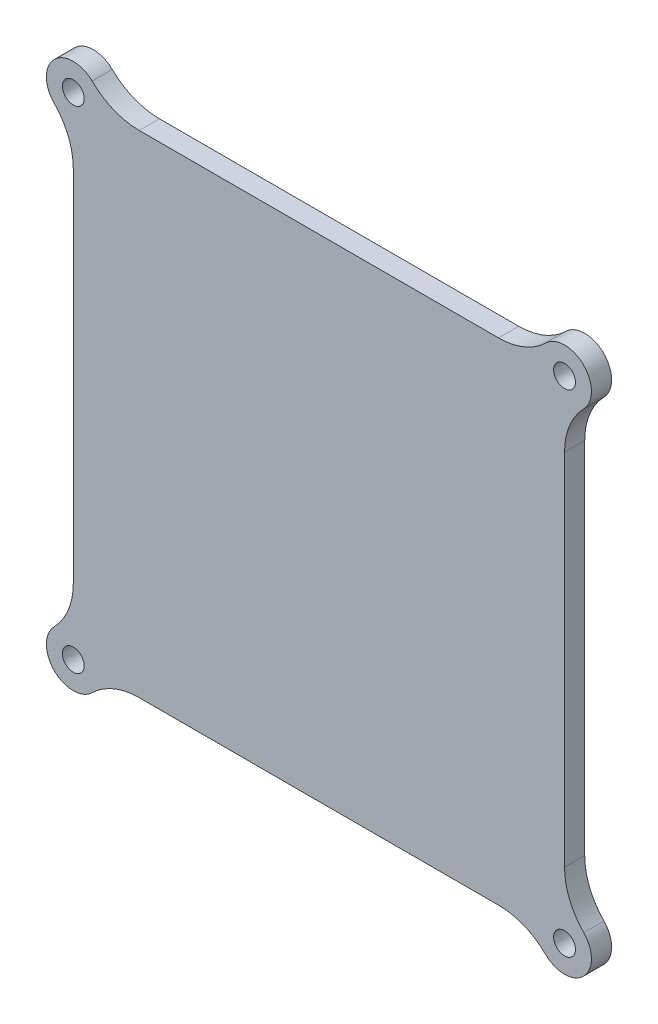
SolidWorks part; units mm, degrees
material "ABS"
ref_plane "Спереди" through (0, 0, 0) normal (0, 0, 1) x (1, 0, 0)
ref_plane "Сверху" through (0, 0, 0) normal (0, 1, 0) x (1, 0, 0)
ref_plane "Справа" through (0, 0, 0) normal (1, 0, 0) x (0, 0, -1)
sketch "Эскиз1" plane through (0, 0, 0) normal (0, 0, 1) x (1, 0, 0)
  line L1 (-36.5161, -36.5161) -> (36.5161, -36.5161)
  line L2 (-36.5161, -36.5161) -> (-36.5161, 36.5161)
  line L3 (-36.5161, 36.5161) -> (36.5161, 36.5161)
  line L4 (36.5161, -36.5161) -> (36.5161, 36.5161)
  line L5 (-36.5161, -36.5161) -> (36.5161, 36.5161) construction
  line L6 (-36.5161, 36.5161) -> (36.5161, -36.5161) construction
  circle A0 centre (-36.5161, 36.5161) radius 1.625
  arc A1 (-32.5161, 36.5161) -> (-36.5161, 32.5161) centre (-36.5161, 36.5161) ccw
  circle A2 centre (36.5161, 36.5161) radius 1.625
  arc A3 (36.5161, 32.5161) -> (32.5161, 36.5161) centre (36.5161, 36.5161) ccw
  circle A4 centre (36.5161, -36.5161) radius 1.625
  arc A5 (32.5161, -36.5161) -> (36.5161, -32.5161) centre (36.5161, -36.5161) ccw
  circle A6 centre (-36.5161, -36.5161) radius 1.625
  arc A7 (-36.5161, -32.5161) -> (-32.5161, -36.5161) centre (-36.5161, -36.5161) ccw
  point P0 (0, 0)
  point P8 (0, 0)
  point P20 (0, 0)
  dimension "D2" = 3.25
  dimension "D3" = 8
  dimension "D1" = 73.0321
  dimension "D4" = 4
extrude "Бобышка-Вытянуть1" add sketch "Эскиз1" along normal blind 3 contours A6 L1 A4 L4 A2 L3 A0 L2 | L3 A1 L2 A0 | L4 A3 L3 A2 | L1 A5 L4 A4 | L2 A7 L1 A6
fillet "Скругление1" radius 10 8 edges at (-32.5161, -36.5161, 1.5) (-36.5161, -32.5161, 1.5) (-32.5161, 36.5161, 1.5) (-36.5161, 32.5161, 1.5) (32.5161, 36.5161, 1.5) (36.5161, 32.5161, 1.5) (36.5161, -32.5161, 1.5) (32.5161, -36.5161, 1.5)
sketch "Эскиз2" plane through (0, 0, 3) normal (0, 0, 1) x (1, 0, 0)
  line L0 (0, 36.5161) -> (0, -36.5161) construction
  line L1 (-26.7181, 36.5161) -> (26.7181, 36.5161) construction
  line L2 (-26.7181, -36.5161) -> (26.7181, -36.5161) construction
